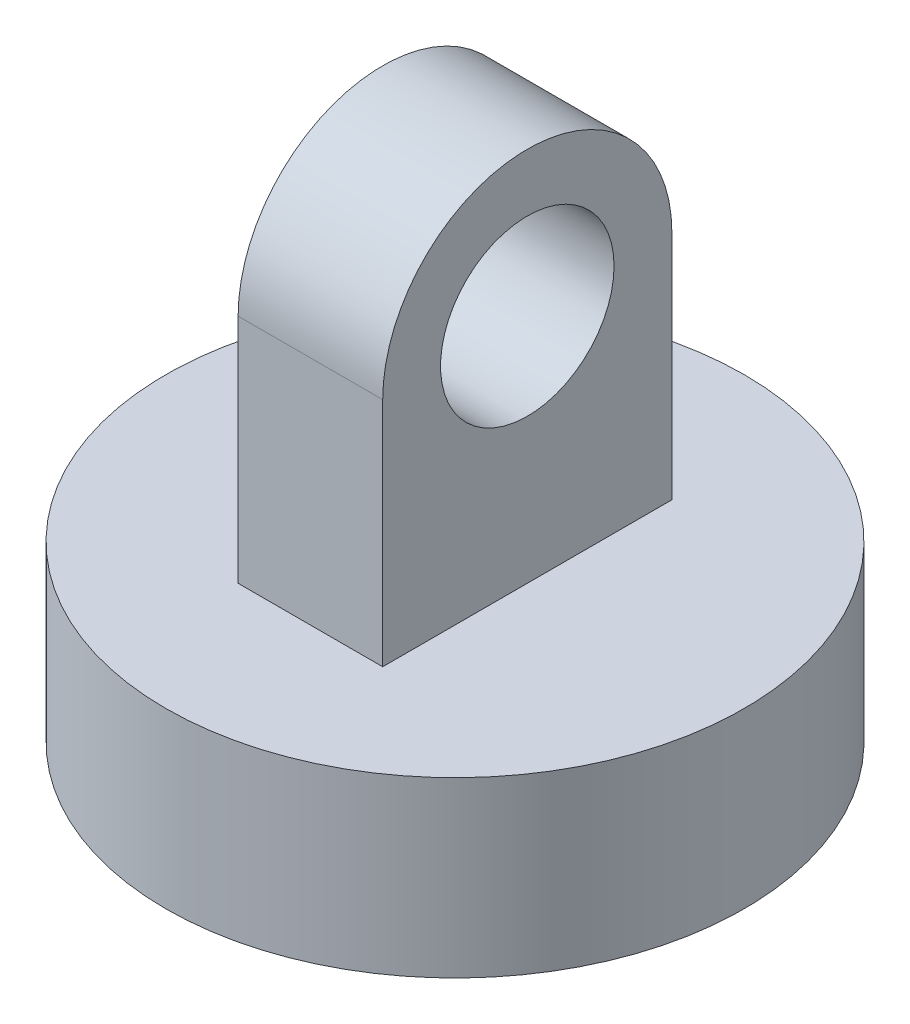
SolidWorks part; units mm, degrees
material "AISI 1020"
ref_plane "Front Plane" through (0, 0, 0) normal (0, 0, 1) x (1, 0, 0)
ref_plane "Top Plane" through (0, 0, 0) normal (0, 1, 0) x (1, 0, 0)
ref_plane "Right Plane" through (0, 0, 0) normal (1, 0, 0) x (0, 0, -1)
sketch "Sketch1" plane through (0, 0, 0) normal (0, 1, 0) x (1, 0, 0)
  circle A0 centre (0, 0) radius 50
  dimension "D1" = 100
extrude "Boss-Extrude1" add sketch "Sketch1" along normal blind 30
sketch "Sketch2" plane through (0, 0, 0) normal (1, 0, 0) x (0, 0, -1)
  line L0 (-25, 70) -> (-25, 30)
  line L1 (50, 30) -> (-50, 30) construction
  line L2 (-25, 30) -> (25, 30)
  line L3 (25, 30) -> (25, 70)
  line L4 (0, 0) -> (0, 70) construction
  arc A0 (25, 70) -> (-25, 70) centre (0, 70) ccw
  circle A1 centre (0, 70) radius 15
  dimension "D1" = 30
  dimension "D2" = 50
  dimension "D3" = 70
extrude "Boss-Extrude2" add sketch "Sketch2" along normal mid plane 25
equation "\"A\"= 100"
equation "\"B\"= 100"
equation "\"C\"= 100"
equation "\"D\"= 100"
equation "\"E\"= 100"
